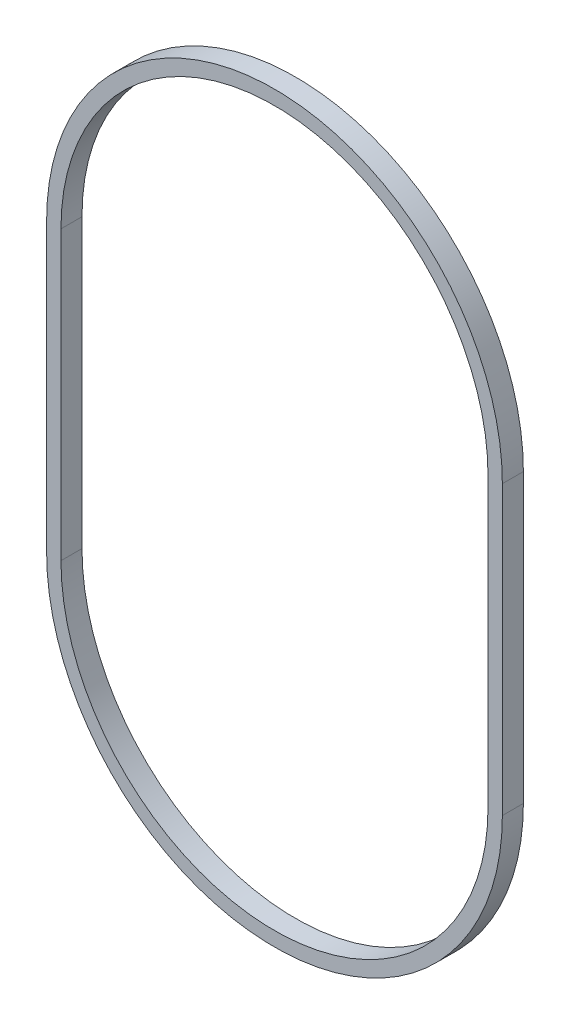
SolidWorks part; units mm, degrees
material "NBR"
ref_plane "Ebene vorne" through (0, 0, 0) normal (0, 0, 1) x (1, 0, 0)
ref_plane "Ebene oben" through (0, 0, 0) normal (0, 1, 0) x (1, 0, 0)
ref_plane "Ebene rechts" through (0, 0, 0) normal (1, 0, 0) x (0, 0, -1)
sketch "Sketch1" plane through (0, 0, 0) normal (0, 0, 1) x (1, 0, 0)
  line L0 (0, -15.04) -> (0, 15.04) construction
  line L1 (-22.35, -15.04) -> (-22.35, 15.04)
  line L2 (22.35, -15.04) -> (22.35, 15.04)
  line L3 (-23.85, -15.04) -> (-23.85, 15.04)
  line L4 (23.85, -15.04) -> (23.85, 15.04)
  arc A0 (-22.35, -15.04) -> (22.35, -15.04) centre (0, -15.04) ccw
  arc A1 (22.35, 15.04) -> (-22.35, 15.04) centre (0, 15.04) ccw
  arc A2 (23.85, 15.04) -> (-23.85, 15.04) centre (0, 15.04) ccw
  arc A3 (-23.85, -15.04) -> (23.85, -15.04) centre (0, -15.04) ccw
  point P2 (0, 0)
  point P8 (0, 0)
  point P10 (0, 0)
  point P16 (0, 0)
  dimension "D2" = 22.35
  dimension "D1" = 15.04
  dimension "D3" = 1.5
extrude "Boss-Extrude1" add sketch "Sketch1" along normal blind 2.2
